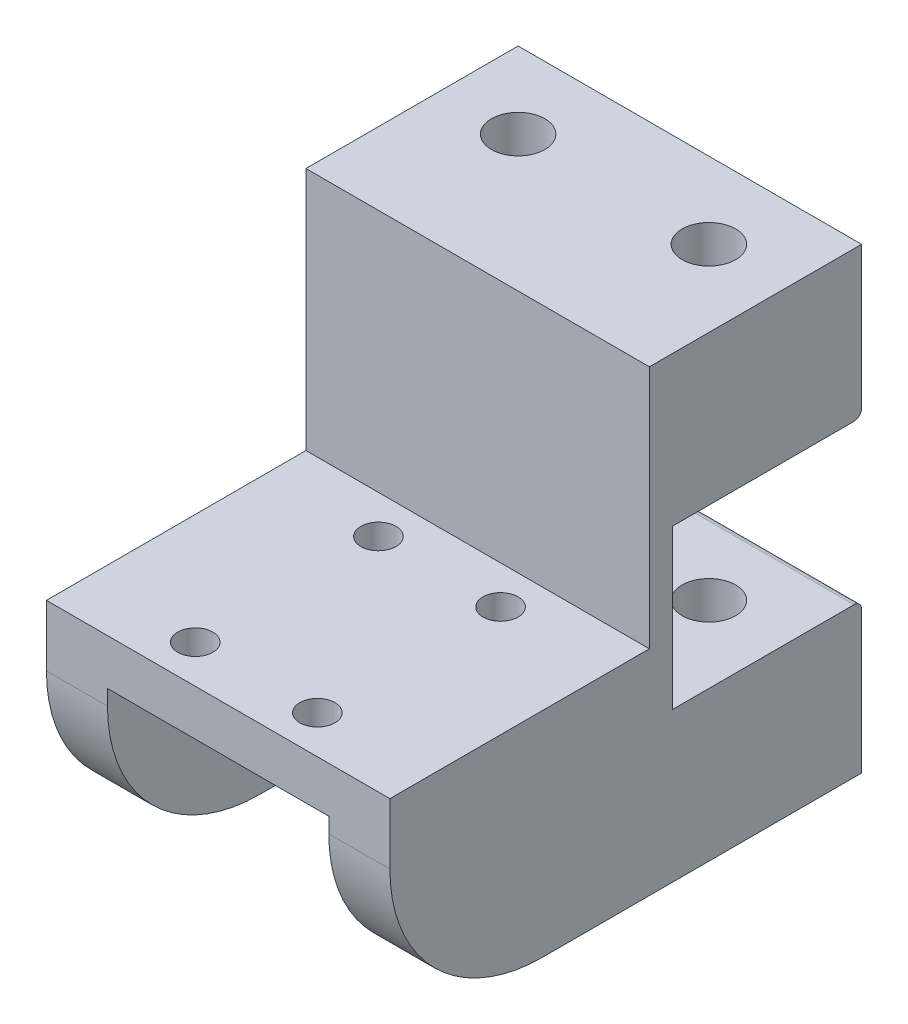
SolidWorks part; units mm, degrees
ref_plane "前视基准面" through (0, 0, 0) normal (0, 0, 1) x (1, 0, 0)
ref_plane "上视基准面" through (0, 0, 0) normal (0, 1, 0) x (1, 0, 0)
ref_plane "右视基准面" through (0, 0, 0) normal (1, 0, 0) x (0, 0, -1)
sketch "草图1" plane through (0, 0, 0) normal (0, 1, 0) x (1, 0, 0)
  line L1 (-11.25, 8.5) -> (11.25, 8.5)
  line L2 (-11.25, 8.5) -> (-11.25, -8.5)
  line L3 (-11.25, -8.5) -> (11.25, -8.5)
  line L4 (11.25, 8.5) -> (11.25, -8.5)
  line L5 (-11.25, 8.5) -> (11.25, -8.5) construction
  line L6 (-11.25, -8.5) -> (11.25, 8.5) construction
  point P0 (0, 0)
  dimension "D1" = 22.5
  dimension "D2" = 17
extrude "凸台-拉伸1" add sketch "草图1" along normal blind 3
sketch "草图2" plane through (0, 3, 0) normal (0, 1, 0) x (1, 0, 0)
  line L0 (11.25, 8.5) -> (-11.25, 8.5) construction
  line L1 (-6.75, 8.5) -> (6.75, 8.5)
  line L2 (-6.75, 8.5) -> (-6.75, -8.5)
  line L3 (-6.75, -8.5) -> (6.75, -8.5)
  line L4 (6.75, 8.5) -> (6.75, -8.5)
  line L5 (-11.25, -8.5) -> (11.25, -8.5) construction
  line L6 (11.25, -8.5) -> (11.25, 8.5) construction
  point P10 (4, 6)
  point P11 (-4, 6)
  point P12 (-4, -6)
  point P13 (4, -6)
  dimension "D1" = 13.5
  dimension "D2" = 4.5
  dimension "D3" = 2.5
  dimension "D4" = 2.75
  dimension "D5" = 2.5
  dimension "D6" = 2.5
  dimension "D7" = 2.5
  dimension "D8" = 2.75
  dimension "D9" = 2.75
  dimension "D10" = 2.75
sketch "草图3" plane through (0, 3, 0) normal (0, 1, 0) x (1, 0, 0)
  point P0 (-4, 6)
  point P3 (4, 6)
  point P6 (-4, -6)
  point P9 (4, -6)
hole_wizard "孔1" positions "草图3" profile "草图4" legacy end condition through all
sketch "草图4" plane through (-4, 3, -6) normal (1, 0, 0) x (0, 0, 1)
  line L0 (0, 0) -> (0, 3)
  line L1 (0, 3) -> (1.15, 3)
  line L2 (1.15, 3) -> (1.15, 0)
  line L3 (1.15, 0) -> (0, 0)
  line L4 (0, 110) -> (0, -10) construction
  dimension "直径" = 2.3
  dimension "深度" = 3
sketch "草图5" plane through (0, 0, -8.5) normal (0, 0, -1) x (-1, 0, 0)
  line L0 (11.25, 3) -> (11.25, 0) construction
  line L1 (-11.25, 0) -> (11.25, 0)
  line L2 (-11.25, 0) -> (-11.25, -4)
  line L3 (-11.25, -4) -> (11.25, -4)
  line L4 (11.25, 0) -> (11.25, -4)
  line L5 (-11.25, 3) -> (11.25, 3)
  line L6 (-11.25, 3) -> (-11.25, 6)
  line L7 (-11.25, 6) -> (11.25, 6)
  line L8 (11.25, 3) -> (11.25, 6)
  line L10 (-11.25, 0) -> (11.25, 0)
  line L11 (-11.25, 0) -> (-11.25, 3)
  line L12 (-11.25, 3) -> (11.25, 3)
  line L13 (11.25, 0) -> (11.25, 3)
  line M13 (-11.25, 0) -> (11.25, 0)
  line M14 (11.25, 0) -> (11.25, 3)
  line M15 (11.25, 3) -> (-11.25, 3)
  line M16 (-11.25, 3) -> (-11.25, 0)
  dimension "D1" = 4
  dimension "D2" = 3
extrude "凸台-拉伸2" add sketch "草图5" along normal blind 1.5 contours L4 L2 L3 M13 | M16 M13 M14 M15 | L8 L7 L6 M15
sketch "草图6" plane through (0, 0, -10) normal (0, 0, -1) x (-1, 0, 0)
  line L1 (-11.25, 6) -> (11.25, 6)
  line L2 (-11.25, 6) -> (-11.25, -4)
  line L3 (-11.25, -4) -> (11.25, -4)
  line L4 (11.25, 6) -> (11.25, -4)
sketch "草图8" plane through (0, 0, -10) normal (0, 0, -1) x (-1, 0, 0)
  line L0 (11.25, 6) -> (11.25, -4) construction
  line L1 (-11.25, -4) -> (11.25, -4)
  line L2 (-11.25, -4) -> (-11.25, -14)
  line L3 (-11.25, -14) -> (11.25, -14)
  line L4 (11.25, -4) -> (11.25, -14)
  line L5 (-11.25, 6) -> (11.25, 6)
  line L6 (-11.25, 6) -> (-11.25, 16)
  line L7 (-11.25, 16) -> (11.25, 16)
  line L8 (11.25, 6) -> (11.25, 16)
  dimension "D1" = 10
  dimension "D2" = 10
extrude "凸台-拉伸3" add sketch "草图8" against normal blind 1.5
sketch "草图9" plane through (-11.25, 0, 0) normal (-1, 0, 0) x (0, 0, 1)
  line L0 (8.5, 3) -> (8.5, 0) construction
  line L1 (-8.5, 0) -> (8.5, 0)
  line L2 (-8.5, 0) -> (-8.5, -14)
  line L3 (-8.5, -14) -> (8.5, -14)
  line L4 (8.5, 0) -> (8.5, -14)
  line L5 (-8.5, -14) -> (-10, -14) construction
extrude "凸台-拉伸4" add sketch "草图9" against normal blind 4
sketch "草图10" plane through (11.25, 0, 0) normal (1, 0, 0) x (0, 0, -1)
  line L1 (8.5, 0) -> (-8.5, 0)
  line L2 (8.5, 0) -> (8.5, -14)
  line L3 (8.5, -14) -> (-8.5, -14)
  line L4 (-8.5, 0) -> (-8.5, -14)
extrude "凸台-拉伸5" add sketch "草图10" against normal blind 4
sketch "草图11" plane through (0, 0, -10) normal (0, 0, -1) x (-1, 0, 0)
  line L0 (11.25, 16) -> (11.25, -14) construction
  line L1 (-11.25, 16) -> (11.25, 16)
  line L2 (-11.25, 16) -> (-11.25, 27)
  line L3 (-11.25, 27) -> (11.25, 27)
  line L4 (11.25, 16) -> (11.25, 27)
  dimension "D1" = 11
extrude "凸台-拉伸6" add sketch "草图11" against normal blind 1.5
sketch "草图12" plane through (0, 0, -10) normal (0, 0, -1) x (-1, 0, 0)
  line L0 (-11.25, -4) -> (11.25, -4) construction
  line L1 (-7.25, -4) -> (7.25, -4)
  line L2 (-7.25, -4) -> (-7.25, -14)
  line L3 (-7.25, -14) -> (7.25, -14)
  line L4 (7.25, -4) -> (7.25, -14)
  line L5 (-11.25, -14) -> (11.25, -14) construction
  line L6 (11.25, 27) -> (11.25, -14) construction
  line L7 (-11.25, 27) -> (-11.25, -14) construction
  line L8 (-7.25, -9) -> (7.25, -9)
  line L9 (0, -9) -> (-7.25, -9)
  line L10 (0, -9) -> (7.25, -9)
  point P15 (3.25, -9)
  point P16 (-3.25, -9)
  dimension "D1" = 4
  dimension "D2" = 4
  dimension "D3" = 4
  dimension "D4" = 4
sketch "草图15" plane through (0, 0, -10) normal (0, 0, -1) x (-1, 0, 0)
  line L0 (11.25, 27) -> (11.25, -14) construction
  line L1 (-11.25, 27) -> (11.25, 27)
  line L2 (-11.25, 27) -> (-11.25, 17)
  line L3 (-11.25, 17) -> (11.25, 17)
  line L4 (11.25, 27) -> (11.25, 17)
  point P7 (7.25, 22)
  point P8 (-7.25, 22)
  dimension "D1" = 10
  dimension "D2" = 5
  dimension "D3" = 4
  dimension "D4" = 4
  dimension "D5" = 5
sketch "草图16" plane through (0, 0, -10) normal (0, 0, -1) x (-1, 0, 0)
  point P0 (-7.25, 22)
  point P3 (7.25, 22)
hole_wizard "孔3" positions "草图16" profile "草图17" legacy end condition through all
sketch "草图17" plane through (7.25, 22, -10) normal (1, 0, 0) x (0, 1, 0)
  line L0 (0, 0) -> (0, 18.5)
  line L1 (0, 18.5) -> (1.65, 18.5)
  line L2 (1.65, 18.5) -> (1.65, 0)
  line L3 (1.65, 0) -> (0, 0)
  line L4 (0, 110) -> (0, -10) construction
  dimension "直径" = 3.3
  dimension "深度" = 18.5
sketch "草图18" plane through (0, 0, -10) normal (0, 0, -1) x (-1, 0, 0)
  line L1 (-11.25, -4) -> (11.25, -4)
  line L2 (-11.25, -4) -> (-11.25, -14)
  line L3 (-11.25, -14) -> (11.25, -14)
  line L4 (11.25, -4) -> (11.25, -14)
  line L5 (-11.25, 17) -> (11.25, 17)
  line L6 (-11.25, 17) -> (-11.25, 27)
  line L7 (-11.25, 27) -> (11.25, 27)
  line L8 (11.25, 17) -> (11.25, 27)
extrude "凸台-拉伸7" add sketch "草图18" along normal blind 2.4 contours L6 L5 L8 L7 | L2 L1 L4 L3
sketch "草图21" plane through (0, 0, -10) normal (0, 0, -1) x (-1, 0, 0)
  line L0 (11.25, 6) -> (11.25, -4) construction
  line L1 (-11.25, -4) -> (11.25, -4)
  line L2 (-11.25, -4) -> (-11.25, -1)
  line L3 (-11.25, -1) -> (11.25, -1)
  line L4 (11.25, -4) -> (11.25, -1)
  dimension "D1" = 3
extrude "凸台-拉伸8" add sketch "草图21" along normal up to surface (2.4 mm away) up to face at (0, -9, -12.4)
sketch "草图22" plane through (0, 0, -10) normal (0, 0, -1) x (-1, 0, 0)
  line L0 (11.25, 17) -> (11.25, -1) construction
  line L1 (-11.25, 17) -> (11.25, 17)
  line L2 (-11.25, 17) -> (-11.25, 9)
  line L3 (-11.25, 9) -> (11.25, 9)
  line L4 (11.25, 17) -> (11.25, 9)
  dimension "D1" = 8
extrude "凸台-拉伸9" add sketch "草图22" along normal up to surface (2.4 mm away) up to face at (0, 22, -12.4)
sketch "草图25" plane through (0, 0, -12.4) normal (0, 0, -1) x (-1, 0, 0)
  line L0 (11.25, 27) -> (11.25, 17) construction
  line L1 (-11.25, 9) -> (11.25, 9)
  line L2 (-11.25, 9) -> (-11.25, 19)
  line L3 (-11.25, 19) -> (11.25, 19)
  line L4 (11.25, 9) -> (11.25, 19)
  line L5 (11.25, -1) -> (11.25, -14) construction
  line L6 (-11.25, -1) -> (11.25, -1)
  line L7 (-11.25, -1) -> (-11.25, -11)
  line L8 (-11.25, -11) -> (11.25, -11)
  line L9 (11.25, -1) -> (11.25, -11)
  line L11 (-11.25, 19) -> (11.25, 19)
  line L12 (-11.25, 19) -> (-11.25, 27)
  line L13 (-11.25, 27) -> (11.25, 27)
  line L14 (11.25, 19) -> (11.25, 27)
  line L15 (-11.25, -11) -> (11.25, -11)
  line L16 (-11.25, -11) -> (-11.25, -14)
  line L17 (-11.25, -14) -> (11.25, -14)
  line L18 (11.25, -11) -> (11.25, -14)
  dimension "D1" = 10
  dimension "D2" = 10
extrude "切除-拉伸1" cut sketch "草图25" against normal through all
sketch "草图26" plane through (0, 0, -12.4) normal (0, 0, -1) x (-1, 0, 0)
  line L1 (-11.25, 19) -> (11.25, 19)
  line L2 (-11.25, 19) -> (-11.25, 9)
  line L3 (-11.25, 9) -> (11.25, 9)
  line L4 (11.25, 19) -> (11.25, 9)
  line L5 (11.25, -1) -> (-11.25, -1)
  line L6 (11.25, -1) -> (11.25, -11)
  line L7 (11.25, -11) -> (-11.25, -11)
  line L8 (-11.25, -1) -> (-11.25, -11)
extrude "凸台-拉伸10" add sketch "草图26" along normal blind 10 contours L2 L1 L4 L3 | L6 L5 L8 L7
fillet "圆角1" radius 10 2 edges at (9.25, -11, 8.5) (-9.25, -11, 8.5)
sketch "草图27" plane through (0, 19, 0) normal (0, 1, 0) x (1, 0, 0)
  line L0 (11.25, 8.5) -> (11.25, 22.4) construction
  line L1 (-11.25, 22.4) -> (11.25, 22.4)
  line L2 (-11.25, 22.4) -> (-11.25, 12.4)
  line L3 (-11.25, 12.4) -> (11.25, 12.4)
  line L4 (11.25, 22.4) -> (11.25, 12.4)
  line L5 (-1.25, 22.4) -> (-1.25, 12.4)
  line L6 (1.25, 22.4) -> (1.25, 12.4)
  line L7 (-11.25, 22.4) -> (-1.25, 12.4)
  line L8 (11.25, 22.4) -> (1.25, 12.4)
  dimension "D1" = 10
  dimension "D2" = 10
  dimension "D3" = 10
sketch "草图28" plane through (0, 19, 0) normal (0, 1, 0) x (1, 0, 0)
  line L0 (-11.25, 22.4) -> (-1.25, 12.4) construction
  line L1 (11.25, 22.4) -> (1.25, 12.4) construction
  point P0 (-6.25, 17.4)
  point P4 (6.25, 17.4)
hole_wizard "孔4" positions "草图28" profile "草图29" legacy end condition through all
sketch "草图29" plane through (-6.25, 19, -17.4) normal (1, 0, 0) x (0, 0, 1)
  line L0 (0, 0) -> (0, 30)
  line L1 (0, 30) -> (1.75, 30)
  line L2 (1.75, 30) -> (1.75, 0)
  line L3 (1.75, 0) -> (0, 0)
  line L4 (0, 110) -> (0, -10) construction
  dimension "直径" = 3.5
  dimension "深度" = 30
sketch "草图30" plane through (11.25, 0, 0) normal (1, 0, 0) x (0, 0, -1)
  line L0 (22.4, 19) -> (22.4, 9) construction
  line L1 (10, 9) -> (22.4, 9)
  line L2 (10, 9) -> (10, 9.2)
  line L3 (10, 9.2) -> (22.4, 9.2)
  line L4 (22.4, 9) -> (22.4, 9.2)
  line L5 (22.4, -1) -> (22.4, -11) construction
  line L6 (10, -1) -> (22.4, -1)
  line L7 (10, -1) -> (10, -1.2)
  line L8 (10, -1.2) -> (22.4, -1.2)
  line L9 (22.4, -1) -> (22.4, -1.2)
  dimension "D1" = 0.2
  dimension "D2" = 0.2
extrude "切除-拉伸2" cut sketch "草图30" against normal through all
fillet "圆角3" radius 0.5 2 edges at (0, -1.2, -22.4) (0, 9.2, -22.4)
